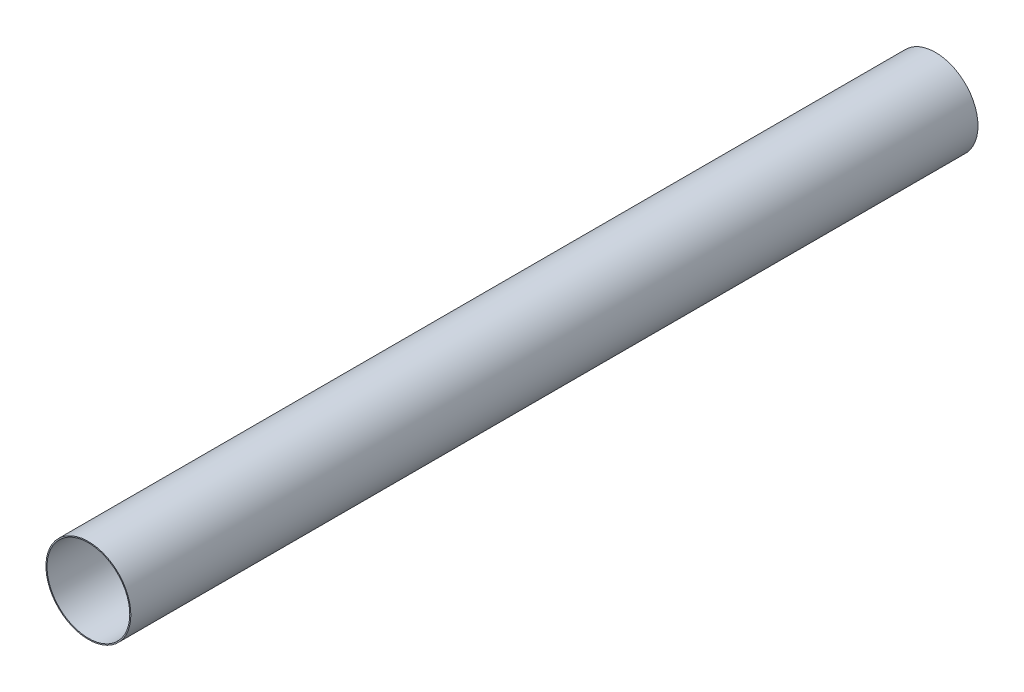
SolidWorks part; units mm, degrees
material "E-Glass Fiber"
ref_plane "Front" through (0, 0, 0) normal (0, 0, 1) x (1, 0, 0)
ref_plane "Top" through (0, 0, 0) normal (0, 1, 0) x (1, 0, 0)
ref_plane "Right" through (0, 0, 0) normal (1, 0, 0) x (0, 0, -1)
sketch "Sketch1" plane through (0, 0, 0) normal (0, 0, 1) x (1, 0, 0)
  circle A0 centre (0, 0) radius 78.2
  circle A1 centre (0, 0) radius 76.2
  dimension "D1" = 156.4
  dimension "D2" = 152.4
extrude "Boss-Extrude1" add sketch "Sketch1" along normal blind 1560
